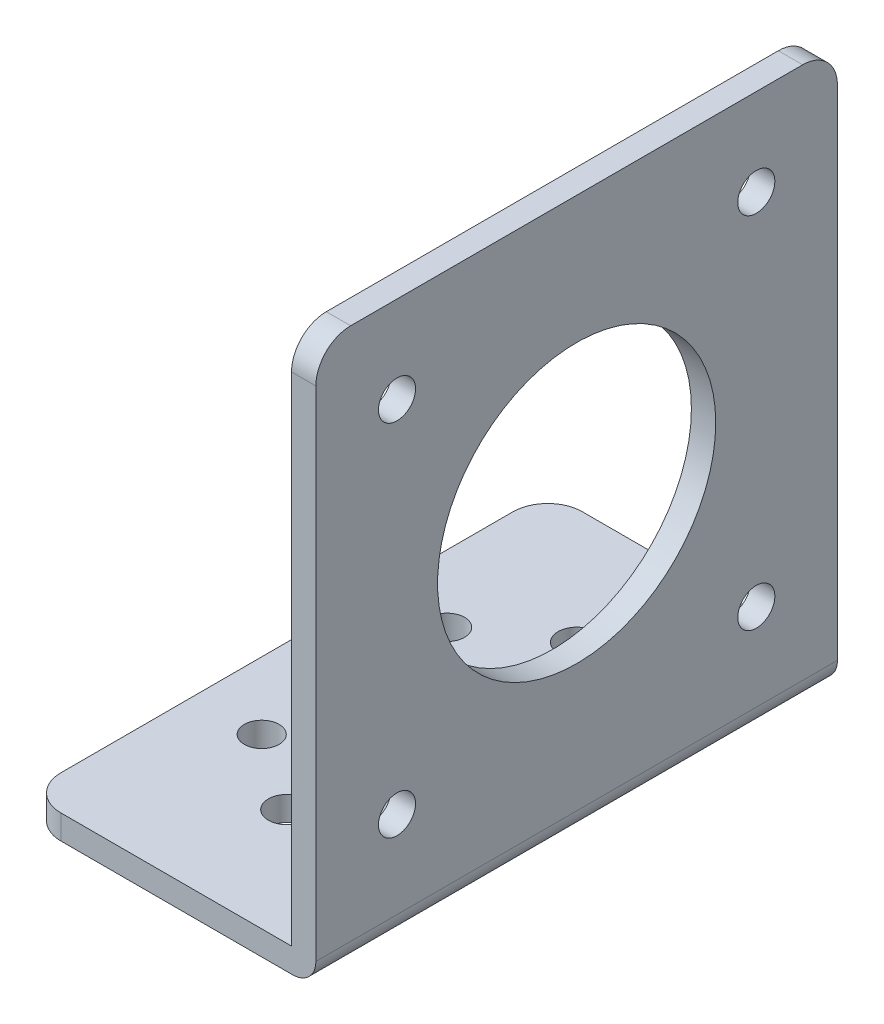
SolidWorks part; units mm, degrees
ref_plane "Front Plane" through (0, 0, 0) normal (0, 0, 1) x (1, 0, 0)
ref_plane "Top Plane" through (0, 0, 0) normal (0, 1, 0) x (1, 0, 0)
ref_plane "Right Plane" through (0, 0, 0) normal (1, 0, 0) x (0, 0, -1)
ref_plane "Plane1" through (2.1, 0, 0) normal (1, 0, 0) x (0, 0, -1)
sketch "Sketch1" plane through (2.1, 0, 0) normal (1, 0, 0) x (0, 0, -1)
  line L0 (22.5, 48) -> (-22.5, 48)
  line L1 (-22.5, 48) -> (-22.5, 0)
  line L2 (-22.5, 0) -> (22.5, 0)
  line L3 (22.5, 0) -> (22.5, 48)
extrude "Boss-Extrude1" add sketch "Sketch1" against normal blind 25
sketch "Sketch2" plane through (0, 0, -22.5) normal (0, 0, -1) x (-1, 0, 0)
  line L0 (22.9, 48) -> (0, 48)
  line L1 (0, 48) -> (0, 2.1)
  line L2 (0, 2.1) -> (22.9, 2.1)
  line L3 (22.9, 2.1) -> (22.9, 48)
extrude "Cut-Extrude1" cut sketch "Sketch2" against normal through all
hole_wizard "Ø24.0 (24) Diameter Hole1" positions "Sketch4" profile "Sketch3" hole size "Ø24.0" standard "ANSI Metric"
sketch "Sketch4" plane through (2.1, 0, 0) normal (1, 0, 0) x (0, 0, -1)
  point P0 (0, 25)
sketch "Sketch3" plane through (2.1, 25, 0) normal (0, 1, 0) x (0, 0, -1)
  line L0 (0, 0) -> (0, 25)
  line L1 (0, 25) -> (12, 25)
  line L2 (12, 25) -> (12, 0)
  line L5 (12, 0) -> (0, 0)
  line L11 (0, -6.35) -> (0, 107.95) construction
  dimension "Thru Hole Dia." = 24
  dimension "Thru Hole Depth" = 25
hole_wizard "Ø3.2 (3.2) Diameter Hole1" positions "Sketch6" profile "Sketch5" hole size "Ø3.2" standard "ANSI Metric"
sketch "Sketch6" plane through (2.1, 0, 0) normal (1, 0, 0) x (0, 0, -1)
  point P0 (15.5, 9.5)
  point P1 (-15.5, 40.5)
  point P2 (15.5, 40.5)
  point P3 (-15.5, 9.5)
sketch "Sketch5" plane through (2.1, 9.5, -15.5) normal (0, 1, 0) x (0, 0, -1)
  line L0 (0, 0) -> (0, 25)
  line L1 (0, 25) -> (1.6, 25)
  line L2 (1.6, 25) -> (1.6, 0)
  line L5 (1.6, 0) -> (0, 0)
  line L11 (0, -6.35) -> (0, 107.95) construction
  dimension "Thru Hole Dia." = 3.2
  dimension "Thru Hole Depth" = 25
hole_wizard "Ø3.2 (3.2) Diameter Hole2" positions "Sketch8" profile "Sketch7" hole size "Ø3.2" standard "ANSI Metric"
sketch "Sketch8" plane through (0, 2.1, 0) normal (0, 1, 0) x (1, 0, 0)
  point P0 (-10.4, 12.5)
  point P1 (-10.4, -12.5)
sketch "Sketch7" plane through (-10.4, 2.1, -12.5) normal (1, 0, 0) x (0, 0, 1)
  line L0 (0, 0) -> (0, 2.1)
  line L1 (0, 2.1) -> (1.6, 2.1)
  line L2 (1.6, 2.1) -> (1.6, 0)
  line L5 (1.6, 0) -> (0, 0)
  line L11 (0, -6.35) -> (0, 107.95) construction
  dimension "Thru Hole Dia." = 3.2
  dimension "Thru Hole Depth" = 2.1
fillet "Fillet1" radius 2 1 edges at (2.1, 0, 0)
fillet "Fillet2" radius 3 4 edges at (-22.9, 1.05, 22.5) (-22.9, 1.05, -22.5) (1.05, 48, 22.5) (1.05, 48, -22.5)
sketch "Sketch9" plane through (0, 2.1, 0) normal (0, 1, 0) x (1, 0, 0)
  line L1 (-17.1029, 8.031) -> (-2.1029, 8.031) construction
  line L2 (-17.1029, 8.031) -> (-17.1029, -7.969) construction
  line L3 (-17.1029, -7.969) -> (-2.1029, -7.969) construction
  line L4 (-2.1029, 8.031) -> (-2.1029, -7.969) construction
  line L5 (-17.1029, 8.031) -> (-2.1029, -7.969) construction
  line L6 (-17.1029, -7.969) -> (-2.1029, 8.031) construction
  point P0 (-9.6029, 0.031)
  point P1 (-2.1029, -7.969)
  point P2 (-17.1029, 8.031)
  point P3 (-17.1029, -7.969)
  point P4 (-2.1029, 8.031)
  dimension "D1" = 15
  dimension "D2" = 16
hole_wizard "Ø3.0 (3) Diameter Hole1" positions "Sketch9" profile "Sketch11" hole size "Ø3.0" standard "ANSI Metric"
sketch "Sketch11" plane through (-2.1029, 2.1, -8.031) normal (1, 0, 0) x (0, 0, 1)
  line L0 (0, 0) -> (0, 2.1)
  line L1 (0, 2.1) -> (1.5, 2.1)
  line L2 (1.5, 2.1) -> (1.5, 0)
  line L5 (1.5, 0) -> (0, 0)
  line L11 (0, -6.35) -> (0, 107.95) construction
  dimension "Thru Hole Dia." = 3
  dimension "Thru Hole Depth" = 2.1
